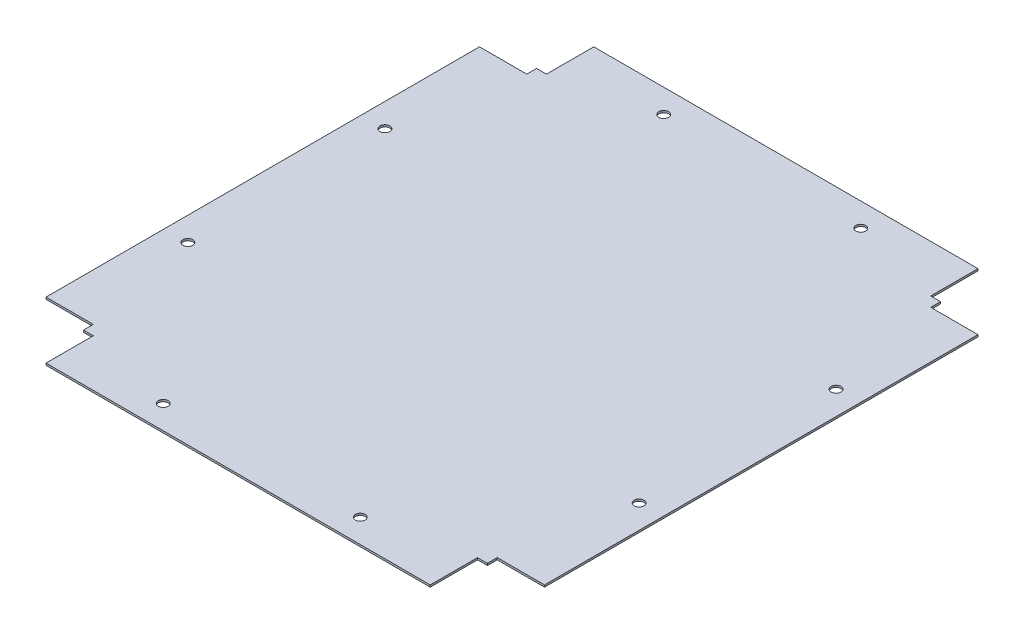
SolidWorks part; units mm, degrees
ref_plane "Front Plane" through (0, 0, 0) normal (0, 0, 1) x (1, 0, 0)
ref_plane "Top Plane" through (0, 0, 0) normal (0, 1, 0) x (1, 0, 0)
ref_plane "Right Plane" through (0, 0, 0) normal (1, 0, 0) x (0, 0, -1)
sketch "Sketch1" plane through (0, 0, 0) normal (0, 1, 0) x (1, 0, 0)
  line L0 (-102.5, 115) -> (-97.5, 115)
  line L1 (-102.5, 115) -> (102.5, 115) construction
  line L2 (-102.5, 115) -> (-102.5, -115) construction
  line L3 (-102.5, -115) -> (102.5, -115) construction
  line L4 (102.5, 115) -> (102.5, -115) construction
  line L5 (-102.5, 115) -> (102.5, -115) construction
  line L6 (-102.5, -115) -> (102.5, 115) construction
  line L7 (-97.5, 115) -> (-97.5, 139)
  line L8 (-97.5, 139) -> (97.5, 139)
  line L9 (97.5, 139) -> (97.5, 115)
  line L10 (97.5, 115) -> (102.5, 115)
  line L11 (102.5, 115) -> (102.5, 110)
  line L12 (102.5, 110) -> (126.5, 110)
  line L13 (126.5, 110) -> (126.5, -110)
  line L14 (126.5, -110) -> (102.5, -110)
  line L15 (102.5, -110) -> (102.5, -115)
  line L16 (102.5, -115) -> (97.5, -115)
  line L17 (97.5, -115) -> (97.5, -139)
  line L18 (97.5, -139) -> (-97.5, -139)
  line L19 (-97.5, -139) -> (-97.5, -115)
  line L20 (-97.5, -115) -> (-102.5, -115)
  line L21 (-102.5, -115) -> (-102.5, -110)
  line L22 (-102.5, -110) -> (-126.5, -110)
  line L23 (-126.5, -110) -> (-126.5, 110)
  line L24 (-126.5, 110) -> (-102.5, 110)
  line L25 (-102.5, 110) -> (-102.5, 115)
  line L26 (-50, 127) -> (50, 127) construction
  line L28 (114.5, 50) -> (114.5, -50) construction
  line L30 (50, -127) -> (-50, -127) construction
  line L32 (-114.5, -50) -> (-114.5, 50) construction
  line L33 (-102.5, 0) -> (-114.5, 0) construction
  line L35 (0, 115) -> (0, 127) construction
  line L37 (102.5, 0) -> (114.5, 0) construction
  line L39 (0, -115) -> (0, -127) construction
  circle A0 centre (-114.5, -50) radius 2.5
  circle A1 centre (-114.5, 50) radius 2.5
  circle A2 centre (-50, 127) radius 2.5
  circle A3 centre (50, 127) radius 2.5
  circle A4 centre (114.5, 50) radius 2.5
  circle A5 centre (114.5, -50) radius 2.5
  circle A6 centre (50, -127) radius 2.5
  circle A7 centre (-50, -127) radius 2.5
  point P0 (0, 0)
  point P29 (0, -115)
  point P31 (-4.7865, -115)
  point P32 (-7.5239, -130.6786)
  point P33 (-1.5359, -115)
  point P34 (0, 0)
  point P35 (0, 0)
  point P36 (0, 0)
  point P37 (0, 0)
  dimension "D3" = 100
  dimension "D9" = 5
  dimension "D1" = 230
  dimension "D2" = 205
  dimension "D4" = 100
  dimension "D5" = 100
  dimension "D6" = 100
  dimension "D7" = 12
  dimension "D8" = 24
  dimension "D10" = 5
extrude "Boss-Extrude1" add sketch "Sketch1" along normal blind 1
